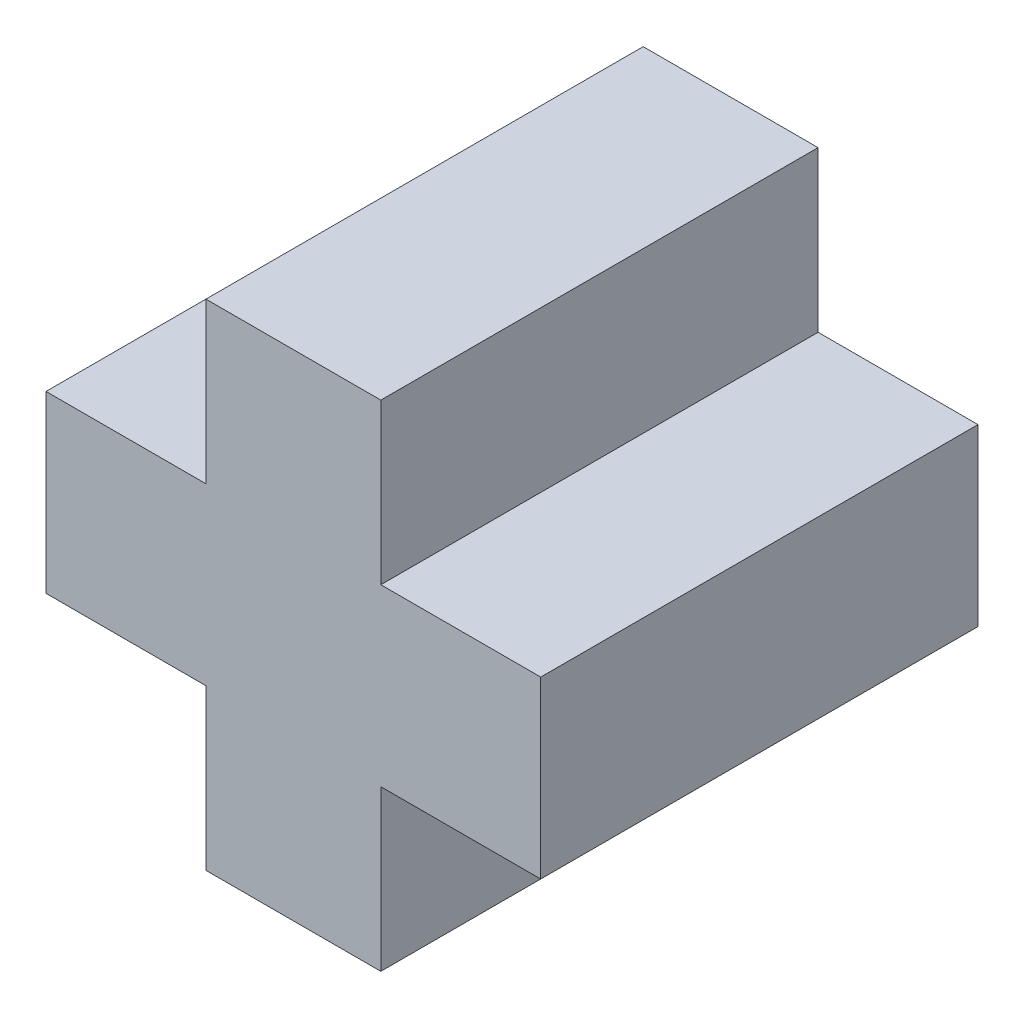
SolidWorks part; units mm, degrees
ref_plane "Front Plane" through (0, 0, 0) normal (0, 0, 1) x (1, 0, 0)
ref_plane "Top Plane" through (0, 0, 0) normal (0, 1, 0) x (1, 0, 0)
ref_plane "Right Plane" through (0, 0, 0) normal (1, 0, 0) x (0, 0, -1)
sketch "Sketch1" plane through (0, 0, 0) normal (0, 0, 1) x (1, 0, 0)
  line L24 (-5, 14.1421) -> (-5, 5)
  line L25 (-5, 5) -> (-14.1421, 5)
  line L26 (-14.1421, 5) -> (-14.1421, -5)
  line L27 (-14.1421, -5) -> (-5, -5)
  line L28 (-5, -5) -> (-5, -14.1421)
  line L29 (-5, -14.1421) -> (5, -14.1421)
  line L30 (5, -14.1421) -> (5, -5)
  line L31 (5, -5) -> (14.1421, -5)
  line L32 (14.1421, -5) -> (14.1421, 5)
  line L33 (14.1421, 5) -> (5, 5)
  line L34 (5, 5) -> (5, 14.1421)
  line L35 (5, 14.1421) -> (-5, 14.1421)
extrude "Boss-Extrude1" add sketch "Sketch1" along normal mid plane 25 contours L31 L32 L33 L34 L35 L24 L25 L26 L27 L28 L29 L30
